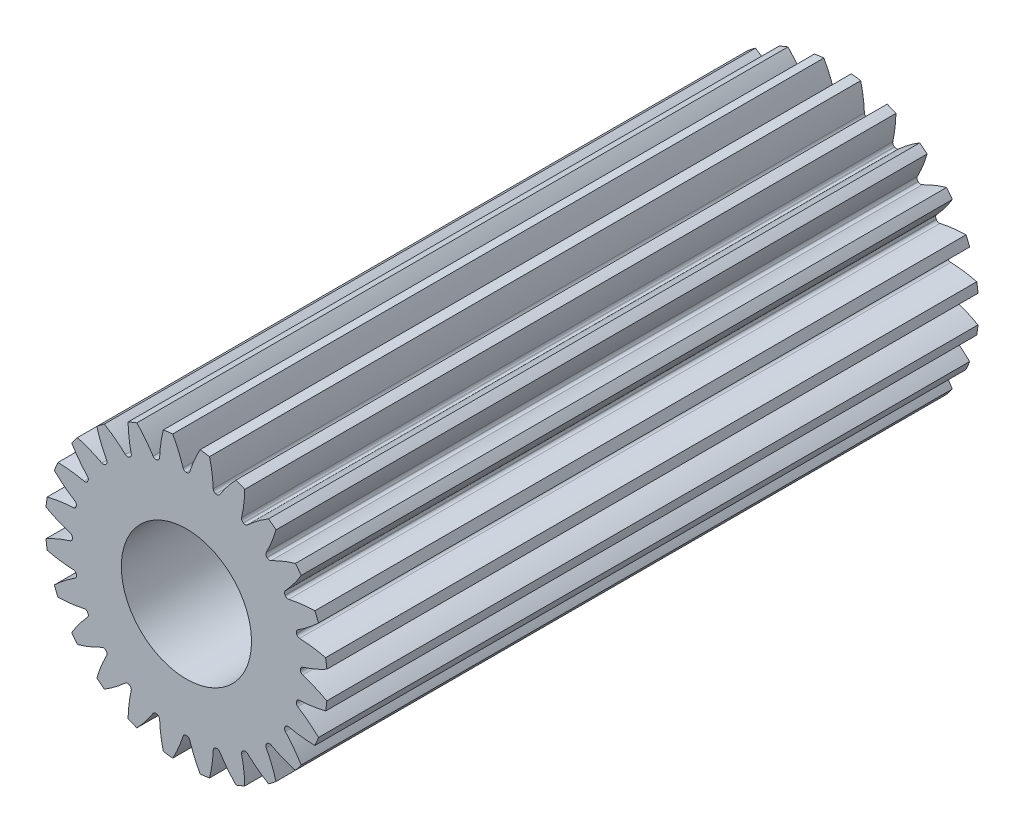
SolidWorks part; units mm, degrees
ref_plane "Front Plane" through (0, 0, 0) normal (0, 0, 1) x (1, 0, 0)
ref_plane "Top Plane" through (0, 0, 0) normal (0, 1, 0) x (1, 0, 0)
ref_plane "Right Plane" through (0, 0, 0) normal (1, 0, 0) x (0, 0, -1)
sketch "Sketch1" plane through (0, 0, 0) normal (0, 0, 1) x (1, 0, 0)
  line L0 (-304.8, 0) -> (304.8, 0) construction
  circle A0 centre (0, 0) radius 6.5 construction
  circle A1 centre (0, 0) radius 6 construction
  circle A2 centre (0, 0) radius 5.25 construction
  circle A3 centre (0, 0) radius 4 construction
  circle A4 centre (0, 0) radius 2 construction
  dimension "D2" = 0.5
  dimension "D3" = 1.25
  dimension "D1" = 1.25
sketch "Sketch2" plane through (0, 0, 0) normal (1, 0, 0) x (0, 0, -1)
  line L0 (0, 0) -> (-3, 0) construction
  line L1 (-3, 0) -> (-7, 0) construction
  dimension "Overall Width" = 7
  dimension "Face Width" = 3
sketch "Sketch4" plane through (0, 0, 0) normal (1, 0, 0) x (0, 0, -1)
  line L0 (-7, 2) -> (-7, 4) construction
  line L1 (-7, 4) -> (-3, 4) construction
  line L2 (-3, 4) -> (-3, 6.5)
  line L3 (-3, 6.5) -> (0, 6.5)
  line L4 (0, 6.5) -> (0, 2)
  line L5 (-3, 4) -> (-3, 0) construction
  line L6 (0, 6.5) -> (0, -6.5) construction
  line L7 (-3, 4) -> (0, 4) construction
  line L8 (-3, 4) -> (-3, 2)
  line L9 (-3, 2) -> (0, 2) construction
  line L10 (0, 2) -> (0, 0)
  line L11 (0, 0) -> (-3, 0)
  line L12 (-7, 2) -> (0, 2) construction
  line L13 (-3, 0) -> (-3, 2)
revolve "Revolve1" add sketch "Sketch4" angle 360 about L1
sketch "Sketch7" plane through (0, 0, 3) normal (0, 0, 1) x (1, 0, 0)
  line L0 (0, 0) -> (0, 6.5) construction
  line L1 (0.3924, 5.9872) -> (0.6056, 6.4717) construction
  line L3 (0.8484, 6.4444) -> (0.7832, 5.9487) construction
  line L4 (0.7832, 5.9487) -> (0.6853, 5.2051) construction
  line L5 (0, 0) -> (0.6853, 5.2051) construction
  line L6 (0.3924, 5.9872) -> (0, 0) construction
  line L7 (0.3924, 5.9872) -> (0.4251, 6.4861) construction
  line L8 (0.3924, 5.9872) -> (0, 0) construction
  circle A0 centre (0, 0) radius 6.5 construction
  arc A1 (-0.0123, 5.25) -> (0.0123, 5.25) centre (0, 0) cw
  circle A2 centre (0, 0) radius 5.25 construction
  arc A3 (-0.3924, 5.9872) -> (0.3924, 5.9872) centre (0, 0) cw construction
  circle A4 centre (0, 0) radius 6 construction
  arc A5 (1.065, 6.4122) -> (0.6309, 6.4693) centre (0, 0) ccw construction
  arc A6 (0.3924, 5.9872) -> (1.1705, 5.8847) centre (0, 0) cw construction
  arc A7 (-0.6309, 6.4693) -> (0.6309, 6.4693) centre (0, 0) cw
  arc A8 (0.1559, 5.3554) -> (0.6309, 6.4693) centre (5.8843, 3.5707) cw
  arc A9 (-0.1559, 5.3554) -> (-0.6309, 6.4693) centre (-5.8843, 3.5707) ccw
  arc A10 (-0.0123, 5.25) -> (-0.1559, 5.3554) centre (-0.0126, 5.4) cw
  arc A11 (0.0123, 5.25) -> (0.1559, 5.3554) centre (0.0126, 5.4) ccw
  point P26 (-0.1237, 5.2485)
  point P29 (0.1237, 5.2485)
  dimension "D4" = 0.15
  dimension "D5" = 6
  dimension "D3" = 20
  dimension "D1" = 1.5708
  dimension "D2" = 0.7854
extrude "Cut-Extrude2" cut sketch "Sketch7" against normal through all
pattern_circular "CirPattern1" count 24 over 360 about axis through (0, 0, 0) along (0, 0, 1) of "Cut-Extrude2"
sketch "Sketch8" plane through (0, 0, 3) normal (0, 0, 1) x (1, 0, 0)
  arc A144 (-1.5366, 5.1326) -> (-2.2838, 6.0856) centre (-6.6079, 1.926) ccw
  arc A145 (-2.2838, 6.0856) -> (-2.6883, 5.918) centre (0, 0) ccw
  arc A146 (-2.6883, 5.918) -> (-2.5427, 4.7158) centre (3.3106, 6.0344) ccw
  arc A147 (-2.6143, 4.5528) -> (-2.5427, 4.7158) centre (-2.689, 4.6829) ccw
  arc A148 (-2.6143, 4.5528) -> (-2.6356, 4.5405) centre (0, 0) ccw
  arc A149 (-2.8127, 4.56) -> (-2.6356, 4.5405) centre (-2.7109, 4.6702) ccw
  arc A150 (-2.8127, 4.56) -> (-3.781, 5.2871) centre (-6.8813, 0.1502) ccw
  arc A151 (-3.781, 5.2871) -> (-4.1284, 5.0206) centre (0, 0) ccw
  arc A152 (-4.1284, 5.0206) -> (-3.6766, 3.897) centre (1.636, 6.6857) ccw
  arc A153 (-3.7036, 3.721) -> (-3.6766, 3.897) centre (-3.8094, 3.8273) ccw
  arc A154 (-3.7036, 3.721) -> (-3.721, 3.7036) centre (0, 0) ccw
  arc A155 (-3.897, 3.6766) -> (-3.721, 3.7036) centre (-3.8273, 3.8094) ccw
  arc A156 (-3.897, 3.6766) -> (-5.0206, 4.1284) centre (-6.6857, -1.636) ccw
  arc A157 (-5.0206, 4.1284) -> (-5.2871, 3.781) centre (0, 0) ccw
  arc A158 (-5.2871, 3.781) -> (-4.56, 2.8127) centre (-0.1502, 6.8813) ccw
  arc A159 (-4.5405, 2.6356) -> (-4.56, 2.8127) centre (-4.6702, 2.7109) ccw
  arc A160 (-4.5405, 2.6356) -> (-4.5528, 2.6143) centre (0, 0) ccw
  arc A161 (-4.7158, 2.5427) -> (-4.5528, 2.6143) centre (-4.6829, 2.689) ccw
  arc A162 (-4.7158, 2.5427) -> (-5.918, 2.6883) centre (-6.0344, -3.3106) ccw
  arc A163 (-5.918, 2.6883) -> (-6.0856, 2.2838) centre (0, 0) ccw
  arc A164 (-6.0856, 2.2838) -> (-5.1326, 1.5366) centre (-1.926, 6.6079) ccw
  arc A165 (-5.0679, 1.3707) -> (-5.1326, 1.5366) centre (-5.2127, 1.4098) ccw
  arc A166 (-5.0679, 1.3707) -> (-5.0743, 1.3469) centre (0, 0) ccw
  arc A167 (-5.2132, 1.2355) -> (-5.0743, 1.3469) centre (-5.2193, 1.3854) ccw
  arc A168 (-5.2132, 1.2355) -> (-6.4122, 1.065) centre (-4.972, -4.7596) ccw
  arc A169 (-6.4122, 1.065) -> (-6.4693, 0.6309) centre (0, 0) ccw
  arc A170 (-6.4693, 0.6309) -> (-5.3554, 0.1559) centre (-3.5707, 5.8843) ccw
  arc A171 (-5.25, 0.0123) -> (-5.3554, 0.1559) centre (-5.4, 0.0126) ccw
  arc A172 (-5.25, 0.0123) -> (-5.25, -0.0123) centre (0, 0) ccw
  arc A173 (-5.3554, -0.1559) -> (-5.25, -0.0123) centre (-5.4, -0.0126) ccw
  arc A174 (-5.3554, -0.1559) -> (-6.4693, -0.6309) centre (-3.5707, -5.8843) ccw
  arc A175 (-6.4693, -0.6309) -> (-6.4122, -1.065) centre (0, 0) ccw
  arc A176 (-6.4122, -1.065) -> (-5.2132, -1.2355) centre (-4.972, 4.7596) ccw
  arc A177 (-5.0743, -1.3469) -> (-5.2132, -1.2355) centre (-5.2193, -1.3854) ccw
  arc A178 (-5.0743, -1.3469) -> (-5.0679, -1.3707) centre (0, 0) ccw
  arc A179 (-5.1326, -1.5366) -> (-5.0679, -1.3707) centre (-5.2127, -1.4098) ccw
  arc A180 (-5.1326, -1.5366) -> (-6.0856, -2.2838) centre (-1.926, -6.6079) ccw
  arc A181 (-6.0856, -2.2838) -> (-5.918, -2.6883) centre (0, 0) ccw
  arc A182 (-5.918, -2.6883) -> (-4.7158, -2.5427) centre (-6.0344, 3.3106) ccw
  arc A183 (-4.5528, -2.6143) -> (-4.7158, -2.5427) centre (-4.6829, -2.689) ccw
  arc A184 (-4.5528, -2.6143) -> (-4.5405, -2.6356) centre (0, 0) ccw
  arc A185 (-4.56, -2.8127) -> (-4.5405, -2.6356) centre (-4.6702, -2.7109) ccw
  arc A186 (-4.56, -2.8127) -> (-5.2871, -3.781) centre (-0.1502, -6.8813) ccw
  arc A187 (-5.2871, -3.781) -> (-5.0206, -4.1284) centre (0, 0) ccw
  arc A188 (-5.0206, -4.1284) -> (-3.897, -3.6766) centre (-6.6857, 1.636) ccw
  arc A189 (-3.721, -3.7036) -> (-3.897, -3.6766) centre (-3.8273, -3.8094) ccw
  arc A190 (-3.721, -3.7036) -> (-3.7036, -3.721) centre (0, 0) ccw
  arc A191 (-3.6766, -3.897) -> (-3.7036, -3.721) centre (-3.8094, -3.8273) ccw
  arc A192 (-3.6766, -3.897) -> (-4.1284, -5.0206) centre (1.636, -6.6857) ccw
  arc A193 (-4.1284, -5.0206) -> (-3.781, -5.2871) centre (0, 0) ccw
  arc A194 (-3.781, -5.2871) -> (-2.8127, -4.56) centre (-6.8813, -0.1502) ccw
  arc A195 (-2.6356, -4.5405) -> (-2.8127, -4.56) centre (-2.7109, -4.6702) ccw
  arc A196 (-2.6356, -4.5405) -> (-2.6143, -4.5528) centre (0, 0) ccw
  arc A197 (-2.5427, -4.7158) -> (-2.6143, -4.5528) centre (-2.689, -4.6829) ccw
  arc A198 (-2.5427, -4.7158) -> (-2.6883, -5.918) centre (3.3106, -6.0344) ccw
  arc A199 (-2.6883, -5.918) -> (-2.2838, -6.0856) centre (0, 0) ccw
  arc A200 (-2.2838, -6.0856) -> (-1.5366, -5.1326) centre (-6.6079, -1.926) ccw
  arc A201 (-1.3707, -5.0679) -> (-1.5366, -5.1326) centre (-1.4098, -5.2127) ccw
  arc A202 (-1.3707, -5.0679) -> (-1.3469, -5.0743) centre (0, 0) ccw
  arc A203 (-1.2355, -5.2132) -> (-1.3469, -5.0743) centre (-1.3854, -5.2193) ccw
  arc A204 (-1.2355, -5.2132) -> (-1.065, -6.4122) centre (4.7596, -4.972) ccw
  arc A205 (-1.065, -6.4122) -> (-0.6309, -6.4693) centre (0, 0) ccw
  arc A206 (-0.6309, -6.4693) -> (-0.1559, -5.3554) centre (-5.8843, -3.5707) ccw
  arc A207 (-0.0123, -5.25) -> (-0.1559, -5.3554) centre (-0.0126, -5.4) ccw
  arc A208 (-0.0123, -5.25) -> (0.0123, -5.25) centre (0, 0) ccw
  arc A209 (0.1559, -5.3554) -> (0.0123, -5.25) centre (0.0126, -5.4) ccw
  arc A210 (0.1559, -5.3554) -> (0.6309, -6.4693) centre (5.8843, -3.5707) ccw
  arc A211 (0.6309, -6.4693) -> (1.065, -6.4122) centre (0, 0) ccw
  arc A212 (1.065, -6.4122) -> (1.2355, -5.2132) centre (-4.7596, -4.972) ccw
  arc A213 (1.3469, -5.0743) -> (1.2355, -5.2132) centre (1.3854, -5.2193) ccw
  arc A214 (1.3469, -5.0743) -> (1.3707, -5.0679) centre (0, 0) ccw
  arc A215 (1.5366, -5.1326) -> (1.3707, -5.0679) centre (1.4098, -5.2127) ccw
  arc A216 (1.5366, -5.1326) -> (2.2838, -6.0856) centre (6.6079, -1.926) ccw
  arc A217 (2.2838, -6.0856) -> (2.6883, -5.918) centre (0, 0) ccw
  arc A218 (2.6883, -5.918) -> (2.5427, -4.7158) centre (-3.3106, -6.0344) ccw
  arc A219 (2.6143, -4.5528) -> (2.5427, -4.7158) centre (2.689, -4.6829) ccw
  arc A220 (2.6143, -4.5528) -> (2.6356, -4.5405) centre (0, 0) ccw
  arc A221 (2.8127, -4.56) -> (2.6356, -4.5405) centre (2.7109, -4.6702) ccw
  arc A222 (2.8127, -4.56) -> (3.781, -5.2871) centre (6.8813, -0.1502) ccw
  arc A223 (3.781, -5.2871) -> (4.1284, -5.0206) centre (0, 0) ccw
  arc A224 (4.1284, -5.0206) -> (3.6766, -3.897) centre (-1.636, -6.6857) ccw
  arc A225 (3.7036, -3.721) -> (3.6766, -3.897) centre (3.8094, -3.8273) ccw
  arc A226 (3.7036, -3.721) -> (3.721, -3.7036) centre (0, 0) ccw
  arc A227 (3.897, -3.6766) -> (3.721, -3.7036) centre (3.8273, -3.8094) ccw
  arc A228 (3.897, -3.6766) -> (5.0206, -4.1284) centre (6.6857, 1.636) ccw
  arc A229 (5.0206, -4.1284) -> (5.2871, -3.781) centre (0, 0) ccw
  arc A230 (5.2871, -3.781) -> (4.56, -2.8127) centre (0.1502, -6.8813) ccw
  arc A231 (4.5405, -2.6356) -> (4.56, -2.8127) centre (4.6702, -2.7109) ccw
  arc A232 (4.5405, -2.6356) -> (4.5528, -2.6143) centre (0, 0) ccw
  arc A233 (4.7158, -2.5427) -> (4.5528, -2.6143) centre (4.6829, -2.689) ccw
  arc A234 (4.7158, -2.5427) -> (5.918, -2.6883) centre (6.0344, 3.3106) ccw
  arc A235 (5.918, -2.6883) -> (6.0856, -2.2838) centre (0, 0) ccw
  arc A236 (6.0856, -2.2838) -> (5.1326, -1.5366) centre (1.926, -6.6079) ccw
  arc A237 (5.0679, -1.3707) -> (5.1326, -1.5366) centre (5.2127, -1.4098) ccw
  arc A238 (5.0679, -1.3707) -> (5.0743, -1.3469) centre (0, 0) ccw
  arc A239 (5.2132, -1.2355) -> (5.0743, -1.3469) centre (5.2193, -1.3854) ccw
  arc A240 (5.2132, -1.2355) -> (6.4122, -1.065) centre (4.972, 4.7596) ccw
  arc A241 (6.4122, -1.065) -> (6.4693, -0.6309) centre (0, 0) ccw
  arc A242 (6.4693, -0.6309) -> (5.3554, -0.1559) centre (3.5707, -5.8843) ccw
  arc A243 (5.25, -0.0123) -> (5.3554, -0.1559) centre (5.4, -0.0126) ccw
  arc A244 (5.25, -0.0123) -> (5.25, 0.0123) centre (0, 0) ccw
  arc A245 (5.3554, 0.1559) -> (5.25, 0.0123) centre (5.4, 0.0126) ccw
  arc A246 (5.3554, 0.1559) -> (6.4693, 0.6309) centre (3.5707, 5.8843) ccw
  arc A247 (6.4693, 0.6309) -> (6.4122, 1.065) centre (0, 0) ccw
  arc A248 (6.4122, 1.065) -> (5.2132, 1.2355) centre (4.972, -4.7596) ccw
  arc A249 (5.0743, 1.3469) -> (5.2132, 1.2355) centre (5.2193, 1.3854) ccw
  arc A250 (5.0743, 1.3469) -> (5.0679, 1.3707) centre (0, 0) ccw
  arc A251 (5.1326, 1.5366) -> (5.0679, 1.3707) centre (5.2127, 1.4098) ccw
  arc A252 (5.1326, 1.5366) -> (6.0856, 2.2838) centre (1.926, 6.6079) ccw
  arc A253 (6.0856, 2.2838) -> (5.918, 2.6883) centre (0, 0) ccw
  arc A254 (5.918, 2.6883) -> (4.7158, 2.5427) centre (6.0344, -3.3106) ccw
  arc A255 (4.5528, 2.6143) -> (4.7158, 2.5427) centre (4.6829, 2.689) ccw
  arc A256 (4.5528, 2.6143) -> (4.5405, 2.6356) centre (0, 0) ccw
  arc A257 (4.56, 2.8127) -> (4.5405, 2.6356) centre (4.6702, 2.7109) ccw
  arc A258 (4.56, 2.8127) -> (5.2871, 3.781) centre (0.1502, 6.8813) ccw
  arc A259 (5.2871, 3.781) -> (5.0206, 4.1284) centre (0, 0) ccw
  arc A260 (5.0206, 4.1284) -> (3.897, 3.6766) centre (6.6857, -1.636) ccw
  arc A261 (3.721, 3.7036) -> (3.897, 3.6766) centre (3.8273, 3.8094) ccw
  arc A262 (3.721, 3.7036) -> (3.7036, 3.721) centre (0, 0) ccw
  arc A263 (3.6766, 3.897) -> (3.7036, 3.721) centre (3.8094, 3.8273) ccw
  arc A264 (3.6766, 3.897) -> (4.1284, 5.0206) centre (-1.636, 6.6857) ccw
  arc A265 (4.1284, 5.0206) -> (3.781, 5.2871) centre (0, 0) ccw
  arc A266 (3.781, 5.2871) -> (2.8127, 4.56) centre (6.8813, 0.1502) ccw
  arc A267 (2.6356, 4.5405) -> (2.8127, 4.56) centre (2.7109, 4.6702) ccw
  arc A268 (2.6356, 4.5405) -> (2.6143, 4.5528) centre (0, 0) ccw
  arc A269 (2.5427, 4.7158) -> (2.6143, 4.5528) centre (2.689, 4.6829) ccw
  arc A270 (2.5427, 4.7158) -> (2.6883, 5.918) centre (-3.3106, 6.0344) ccw
  arc A271 (2.6883, 5.918) -> (2.2838, 6.0856) centre (0, 0) ccw
  arc A272 (2.2838, 6.0856) -> (1.5366, 5.1326) centre (6.6079, 1.926) ccw
  arc A273 (1.3707, 5.0679) -> (1.5366, 5.1326) centre (1.4098, 5.2127) ccw
  arc A274 (1.3707, 5.0679) -> (1.3469, 5.0743) centre (0, 0) ccw
  arc A275 (1.2355, 5.2132) -> (1.3469, 5.0743) centre (1.3854, 5.2193) ccw
  arc A276 (1.2355, 5.2132) -> (1.065, 6.4122) centre (-4.7596, 4.972) ccw
  arc A277 (1.065, 6.4122) -> (0.6309, 6.4693) centre (0, 0) ccw
  arc A278 (0.6309, 6.4693) -> (0.1559, 5.3554) centre (5.8843, 3.5707) ccw
  arc A279 (0.0123, 5.25) -> (0.1559, 5.3554) centre (0.0126, 5.4) ccw
  arc A280 (0.0123, 5.25) -> (-0.0123, 5.25) centre (0, 0) ccw
  arc A281 (-0.1559, 5.3554) -> (-0.0123, 5.25) centre (-0.0126, 5.4) ccw
  arc A282 (-0.1559, 5.3554) -> (-0.6309, 6.4693) centre (-5.8843, 3.5707) ccw
  arc A283 (-0.6309, 6.4693) -> (-1.065, 6.4122) centre (0, 0) ccw
  arc A284 (-1.065, 6.4122) -> (-1.2355, 5.2132) centre (4.7596, 4.972) ccw
  arc A285 (-1.3469, 5.0743) -> (-1.2355, 5.2132) centre (-1.3854, 5.2193) ccw
  arc A286 (-1.3469, 5.0743) -> (-1.3707, 5.0679) centre (0, 0) ccw
  arc A287 (-1.5366, 5.1326) -> (-1.3707, 5.0679) centre (-1.4098, 5.2127) ccw
  arc A288 (-1.5366, 5.1326) -> (-2.2838, 6.0856) centre (-6.6079, 1.926) ccw
  arc A289 (-2.2838, 6.0856) -> (-2.6883, 5.918) centre (0, 0) ccw
  arc A290 (-2.6883, 5.918) -> (-2.5427, 4.7158) centre (3.3106, 6.0344) ccw
  arc A291 (-2.6143, 4.5528) -> (-2.5427, 4.7158) centre (-2.689, 4.6829) ccw
  arc A292 (-2.6143, 4.5528) -> (-2.6356, 4.5405) centre (0, 0) ccw
  arc A293 (-2.8127, 4.56) -> (-2.6356, 4.5405) centre (-2.7109, 4.6702) ccw
  arc A294 (-2.8127, 4.56) -> (-3.781, 5.2871) centre (-6.8813, 0.1502) ccw
  arc A295 (-3.781, 5.2871) -> (-4.1284, 5.0206) centre (0, 0) ccw
  arc A296 (-4.1284, 5.0206) -> (-3.6766, 3.897) centre (1.636, 6.6857) ccw
  arc A297 (-3.7036, 3.721) -> (-3.6766, 3.897) centre (-3.8094, 3.8273) ccw
  arc A298 (-3.7036, 3.721) -> (-3.721, 3.7036) centre (0, 0) ccw
  arc A299 (-3.897, 3.6766) -> (-3.721, 3.7036) centre (-3.8273, 3.8094) ccw
  arc A300 (-3.897, 3.6766) -> (-5.0206, 4.1284) centre (-6.6857, -1.636) ccw
  arc A301 (-5.0206, 4.1284) -> (-5.2871, 3.781) centre (0, 0) ccw
  arc A302 (-5.2871, 3.781) -> (-4.56, 2.8127) centre (-0.1502, 6.8813) ccw
  arc A303 (-4.5405, 2.6356) -> (-4.56, 2.8127) centre (-4.6702, 2.7109) ccw
  arc A304 (-4.5405, 2.6356) -> (-4.5528, 2.6143) centre (0, 0) ccw
  arc A305 (-4.7158, 2.5427) -> (-4.5528, 2.6143) centre (-4.6829, 2.689) ccw
  arc A306 (-4.7158, 2.5427) -> (-5.918, 2.6883) centre (-6.0344, -3.3106) ccw
  arc A307 (-5.918, 2.6883) -> (-6.0856, 2.2838) centre (0, 0) ccw
  arc A308 (-6.0856, 2.2838) -> (-5.1326, 1.5366) centre (-1.926, 6.6079) ccw
  arc A309 (-5.0679, 1.3707) -> (-5.1326, 1.5366) centre (-5.2127, 1.4098) ccw
  arc A310 (-5.0679, 1.3707) -> (-5.0743, 1.3469) centre (0, 0) ccw
  arc A311 (-5.2132, 1.2355) -> (-5.0743, 1.3469) centre (-5.2193, 1.3854) ccw
  arc A312 (-5.2132, 1.2355) -> (-6.4122, 1.065) centre (-4.972, -4.7596) ccw
  arc A313 (-6.4122, 1.065) -> (-6.4693, 0.6309) centre (0, 0) ccw
  arc A314 (-6.4693, 0.6309) -> (-5.3554, 0.1559) centre (-3.5707, 5.8843) ccw
  arc A315 (-5.25, 0.0123) -> (-5.3554, 0.1559) centre (-5.4, 0.0126) ccw
  arc A316 (-5.25, 0.0123) -> (-5.25, -0.0123) centre (0, 0) ccw
  arc A317 (-5.3554, -0.1559) -> (-5.25, -0.0123) centre (-5.4, -0.0126) ccw
  arc A318 (-5.3554, -0.1559) -> (-6.4693, -0.6309) centre (-3.5707, -5.8843) ccw
  arc A319 (-6.4693, -0.6309) -> (-6.4122, -1.065) centre (0, 0) ccw
  arc A320 (-6.4122, -1.065) -> (-5.2132, -1.2355) centre (-4.972, 4.7596) ccw
  arc A321 (-5.0743, -1.3469) -> (-5.2132, -1.2355) centre (-5.2193, -1.3854) ccw
  arc A322 (-5.0743, -1.3469) -> (-5.0679, -1.3707) centre (0, 0) ccw
  arc A323 (-5.1326, -1.5366) -> (-5.0679, -1.3707) centre (-5.2127, -1.4098) ccw
  arc A324 (-5.1326, -1.5366) -> (-6.0856, -2.2838) centre (-1.926, -6.6079) ccw
  arc A325 (-6.0856, -2.2838) -> (-5.918, -2.6883) centre (0, 0) ccw
  arc A326 (-5.918, -2.6883) -> (-4.7158, -2.5427) centre (-6.0344, 3.3106) ccw
  arc A327 (-4.5528, -2.6143) -> (-4.7158, -2.5427) centre (-4.6829, -2.689) ccw
  arc A328 (-4.5528, -2.6143) -> (-4.5405, -2.6356) centre (0, 0) ccw
  arc A329 (-4.56, -2.8127) -> (-4.5405, -2.6356) centre (-4.6702, -2.7109) ccw
  arc A330 (-4.56, -2.8127) -> (-5.2871, -3.781) centre (-0.1502, -6.8813) ccw
  arc A331 (-5.2871, -3.781) -> (-5.0206, -4.1284) centre (0, 0) ccw
  arc A332 (-5.0206, -4.1284) -> (-3.897, -3.6766) centre (-6.6857, 1.636) ccw
  arc A333 (-3.721, -3.7036) -> (-3.897, -3.6766) centre (-3.8273, -3.8094) ccw
  arc A334 (-3.721, -3.7036) -> (-3.7036, -3.721) centre (0, 0) ccw
  arc A335 (-3.6766, -3.897) -> (-3.7036, -3.721) centre (-3.8094, -3.8273) ccw
  arc A336 (-3.6766, -3.897) -> (-4.1284, -5.0206) centre (1.636, -6.6857) ccw
  arc A337 (-4.1284, -5.0206) -> (-3.781, -5.2871) centre (0, 0) ccw
  arc A338 (-3.781, -5.2871) -> (-2.8127, -4.56) centre (-6.8813, -0.1502) ccw
  arc A339 (-2.6356, -4.5405) -> (-2.8127, -4.56) centre (-2.7109, -4.6702) ccw
  arc A340 (-2.6356, -4.5405) -> (-2.6143, -4.5528) centre (0, 0) ccw
  arc A341 (-2.5427, -4.7158) -> (-2.6143, -4.5528) centre (-2.689, -4.6829) ccw
  arc A342 (-2.5427, -4.7158) -> (-2.6883, -5.918) centre (3.3106, -6.0344) ccw
  arc A343 (-2.6883, -5.918) -> (-2.2838, -6.0856) centre (0, 0) ccw
  arc A344 (-2.2838, -6.0856) -> (-1.5366, -5.1326) centre (-6.6079, -1.926) ccw
  arc A345 (-1.3707, -5.0679) -> (-1.5366, -5.1326) centre (-1.4098, -5.2127) ccw
  arc A346 (-1.3707, -5.0679) -> (-1.3469, -5.0743) centre (0, 0) ccw
  arc A347 (-1.2355, -5.2132) -> (-1.3469, -5.0743) centre (-1.3854, -5.2193) ccw
  arc A348 (-1.2355, -5.2132) -> (-1.065, -6.4122) centre (4.7596, -4.972) ccw
  arc A349 (-1.065, -6.4122) -> (-0.6309, -6.4693) centre (0, 0) ccw
  arc A350 (-0.6309, -6.4693) -> (-0.1559, -5.3554) centre (-5.8843, -3.5707) ccw
  arc A351 (-0.0123, -5.25) -> (-0.1559, -5.3554) centre (-0.0126, -5.4) ccw
  arc A352 (-0.0123, -5.25) -> (0.0123, -5.25) centre (0, 0) ccw
  arc A353 (0.1559, -5.3554) -> (0.0123, -5.25) centre (0.0126, -5.4) ccw
  arc A354 (0.1559, -5.3554) -> (0.6309, -6.4693) centre (5.8843, -3.5707) ccw
  arc A355 (0.6309, -6.4693) -> (1.065, -6.4122) centre (0, 0) ccw
  arc A356 (1.065, -6.4122) -> (1.2355, -5.2132) centre (-4.7596, -4.972) ccw
  arc A357 (1.3469, -5.0743) -> (1.2355, -5.2132) centre (1.3854, -5.2193) ccw
  arc A358 (1.3469, -5.0743) -> (1.3707, -5.0679) centre (0, 0) ccw
  arc A359 (1.5366, -5.1326) -> (1.3707, -5.0679) centre (1.4098, -5.2127) ccw
  arc A360 (1.5366, -5.1326) -> (2.2838, -6.0856) centre (6.6079, -1.926) ccw
  arc A361 (2.2838, -6.0856) -> (2.6883, -5.918) centre (0, 0) ccw
  arc A362 (2.6883, -5.918) -> (2.5427, -4.7158) centre (-3.3106, -6.0344) ccw
  arc A363 (2.6143, -4.5528) -> (2.5427, -4.7158) centre (2.689, -4.6829) ccw
  arc A364 (2.6143, -4.5528) -> (2.6356, -4.5405) centre (0, 0) ccw
  arc A365 (2.8127, -4.56) -> (2.6356, -4.5405) centre (2.7109, -4.6702) ccw
  arc A366 (2.8127, -4.56) -> (3.781, -5.2871) centre (6.8813, -0.1502) ccw
  arc A367 (3.781, -5.2871) -> (4.1284, -5.0206) centre (0, 0) ccw
  arc A368 (4.1284, -5.0206) -> (3.6766, -3.897) centre (-1.636, -6.6857) ccw
  arc A369 (3.7036, -3.721) -> (3.6766, -3.897) centre (3.8094, -3.8273) ccw
  arc A370 (3.7036, -3.721) -> (3.721, -3.7036) centre (0, 0) ccw
  arc A371 (3.897, -3.6766) -> (3.721, -3.7036) centre (3.8273, -3.8094) ccw
  arc A372 (3.897, -3.6766) -> (5.0206, -4.1284) centre (6.6857, 1.636) ccw
  arc A373 (5.0206, -4.1284) -> (5.2871, -3.781) centre (0, 0) ccw
  arc A374 (5.2871, -3.781) -> (4.56, -2.8127) centre (0.1502, -6.8813) ccw
  arc A375 (4.5405, -2.6356) -> (4.56, -2.8127) centre (4.6702, -2.7109) ccw
  arc A376 (4.5405, -2.6356) -> (4.5528, -2.6143) centre (0, 0) ccw
  arc A377 (4.7158, -2.5427) -> (4.5528, -2.6143) centre (4.6829, -2.689) ccw
  arc A378 (4.7158, -2.5427) -> (5.918, -2.6883) centre (6.0344, 3.3106) ccw
  arc A379 (5.918, -2.6883) -> (6.0856, -2.2838) centre (0, 0) ccw
  arc A380 (6.0856, -2.2838) -> (5.1326, -1.5366) centre (1.926, -6.6079) ccw
  arc A381 (5.0679, -1.3707) -> (5.1326, -1.5366) centre (5.2127, -1.4098) ccw
  arc A382 (5.0679, -1.3707) -> (5.0743, -1.3469) centre (0, 0) ccw
  arc A383 (5.2132, -1.2355) -> (5.0743, -1.3469) centre (5.2193, -1.3854) ccw
  arc A384 (5.2132, -1.2355) -> (6.4122, -1.065) centre (4.972, 4.7596) ccw
  arc A385 (6.4122, -1.065) -> (6.4693, -0.6309) centre (0, 0) ccw
  arc A386 (6.4693, -0.6309) -> (5.3554, -0.1559) centre (3.5707, -5.8843) ccw
  arc A387 (5.25, -0.0123) -> (5.3554, -0.1559) centre (5.4, -0.0126) ccw
  arc A388 (5.25, -0.0123) -> (5.25, 0.0123) centre (0, 0) ccw
  arc A389 (5.3554, 0.1559) -> (5.25, 0.0123) centre (5.4, 0.0126) ccw
  arc A390 (5.3554, 0.1559) -> (6.4693, 0.6309) centre (3.5707, 5.8843) ccw
  arc A391 (6.4693, 0.6309) -> (6.4122, 1.065) centre (0, 0) ccw
  arc A392 (6.4122, 1.065) -> (5.2132, 1.2355) centre (4.972, -4.7596) ccw
  arc A393 (5.0743, 1.3469) -> (5.2132, 1.2355) centre (5.2193, 1.3854) ccw
  arc A394 (5.0743, 1.3469) -> (5.0679, 1.3707) centre (0, 0) ccw
  arc A395 (5.1326, 1.5366) -> (5.0679, 1.3707) centre (5.2127, 1.4098) ccw
  arc A396 (5.1326, 1.5366) -> (6.0856, 2.2838) centre (1.926, 6.6079) ccw
  arc A397 (6.0856, 2.2838) -> (5.918, 2.6883) centre (0, 0) ccw
  arc A398 (5.918, 2.6883) -> (4.7158, 2.5427) centre (6.0344, -3.3106) ccw
  arc A399 (4.5528, 2.6143) -> (4.7158, 2.5427) centre (4.6829, 2.689) ccw
  arc A400 (4.5528, 2.6143) -> (4.5405, 2.6356) centre (0, 0) ccw
  arc A401 (4.56, 2.8127) -> (4.5405, 2.6356) centre (4.6702, 2.7109) ccw
  arc A402 (4.56, 2.8127) -> (5.2871, 3.781) centre (0.1502, 6.8813) ccw
  arc A403 (5.2871, 3.781) -> (5.0206, 4.1284) centre (0, 0) ccw
  arc A404 (5.0206, 4.1284) -> (3.897, 3.6766) centre (6.6857, -1.636) ccw
  arc A405 (3.721, 3.7036) -> (3.897, 3.6766) centre (3.8273, 3.8094) ccw
  arc A406 (3.721, 3.7036) -> (3.7036, 3.721) centre (0, 0) ccw
  arc A407 (3.6766, 3.897) -> (3.7036, 3.721) centre (3.8094, 3.8273) ccw
  arc A408 (3.6766, 3.897) -> (4.1284, 5.0206) centre (-1.636, 6.6857) ccw
  arc A409 (4.1284, 5.0206) -> (3.781, 5.2871) centre (0, 0) ccw
  arc A410 (3.781, 5.2871) -> (2.8127, 4.56) centre (6.8813, 0.1502) ccw
  arc A411 (2.6356, 4.5405) -> (2.8127, 4.56) centre (2.7109, 4.6702) ccw
  arc A412 (2.6356, 4.5405) -> (2.6143, 4.5528) centre (0, 0) ccw
  arc A413 (2.5427, 4.7158) -> (2.6143, 4.5528) centre (2.689, 4.6829) ccw
  arc A414 (2.5427, 4.7158) -> (2.6883, 5.918) centre (-3.3106, 6.0344) ccw
  arc A415 (2.6883, 5.918) -> (2.2838, 6.0856) centre (0, 0) ccw
  arc A416 (2.2838, 6.0856) -> (1.5366, 5.1326) centre (6.6079, 1.926) ccw
  arc A417 (1.3707, 5.0679) -> (1.5366, 5.1326) centre (1.4098, 5.2127) ccw
  arc A418 (1.3707, 5.0679) -> (1.3469, 5.0743) centre (0, 0) ccw
  arc A419 (1.2355, 5.2132) -> (1.3469, 5.0743) centre (1.3854, 5.2193) ccw
  arc A420 (1.2355, 5.2132) -> (1.065, 6.4122) centre (-4.7596, 4.972) ccw
  arc A421 (1.065, 6.4122) -> (0.6309, 6.4693) centre (0, 0) ccw
  arc A422 (0.6309, 6.4693) -> (0.1559, 5.3554) centre (5.8843, 3.5707) ccw
  arc A423 (0.0123, 5.25) -> (0.1559, 5.3554) centre (0.0126, 5.4) ccw
  arc A424 (0.0123, 5.25) -> (-0.0123, 5.25) centre (0, 0) ccw
  arc A425 (-0.1559, 5.3554) -> (-0.0123, 5.25) centre (-0.0126, 5.4) ccw
  arc A426 (-0.1559, 5.3554) -> (-0.6309, 6.4693) centre (-5.8843, 3.5707) ccw
  arc A427 (-0.6309, 6.4693) -> (-1.065, 6.4122) centre (0, 0) ccw
  arc A428 (-1.065, 6.4122) -> (-1.2355, 5.2132) centre (4.7596, 4.972) ccw
  arc A429 (-1.3469, 5.0743) -> (-1.2355, 5.2132) centre (-1.3854, 5.2193) ccw
  arc A430 (-1.3469, 5.0743) -> (-1.3707, 5.0679) centre (0, 0) ccw
  arc A431 (-1.5366, 5.1326) -> (-1.3707, 5.0679) centre (-1.4098, 5.2127) ccw
  dimension "D1" = 0
extrude "Boss-Extrude1" add sketch "Sketch8" along normal blind 27
sketch "Sketch9" plane through (0, 0, 0) normal (0, 0, -1) x (-1, 0, 0)
  line L0 (-1.4283, 1.4) -> (1.4283, 1.4)
  circle A0 centre (0, 0) radius 2 construction
  arc A1 (-1.4283, 1.4) -> (1.4283, 1.4) centre (0, 0) ccw
  point P6 (0, 0)
  point P7 (0, 0)
  dimension "D1" = 3.4
  dimension "D2" = 4
extrude "Cut-Extrude3" cut sketch "Sketch9" against normal blind 10
sketch "Sketch10" plane through (0, 0, 30) normal (0, 0, 1) x (1, 0, 0)
  circle A0 centre (0, 0) radius 3
  dimension "D1" = 6
extrude "Cut-Extrude4" cut sketch "Sketch10" against normal blind 10
equation "\"D1@Sketch1\"=2.5*(\"Pitch Dia.@Sketch1\"/\"Number of Teeth@Sketch1\")"
equation "\"D1@CirPattern1\"=\"Number of Teeth@Sketch1\""
equation "\"D1@Sketch7\"=3.14159*(\"Pitch Dia.@Sketch1\"/\"Number of Teeth@Sketch1\")"
equation "\"D2@Sketch7\"=\"D1@Sketch7\"/2"
equation "\"D4@Sketch7\"=\"D1@Sketch7\"*.0955"
equation "\"D5@Sketch7\"=\"Pitch Dia.@Sketch1\"/2"
